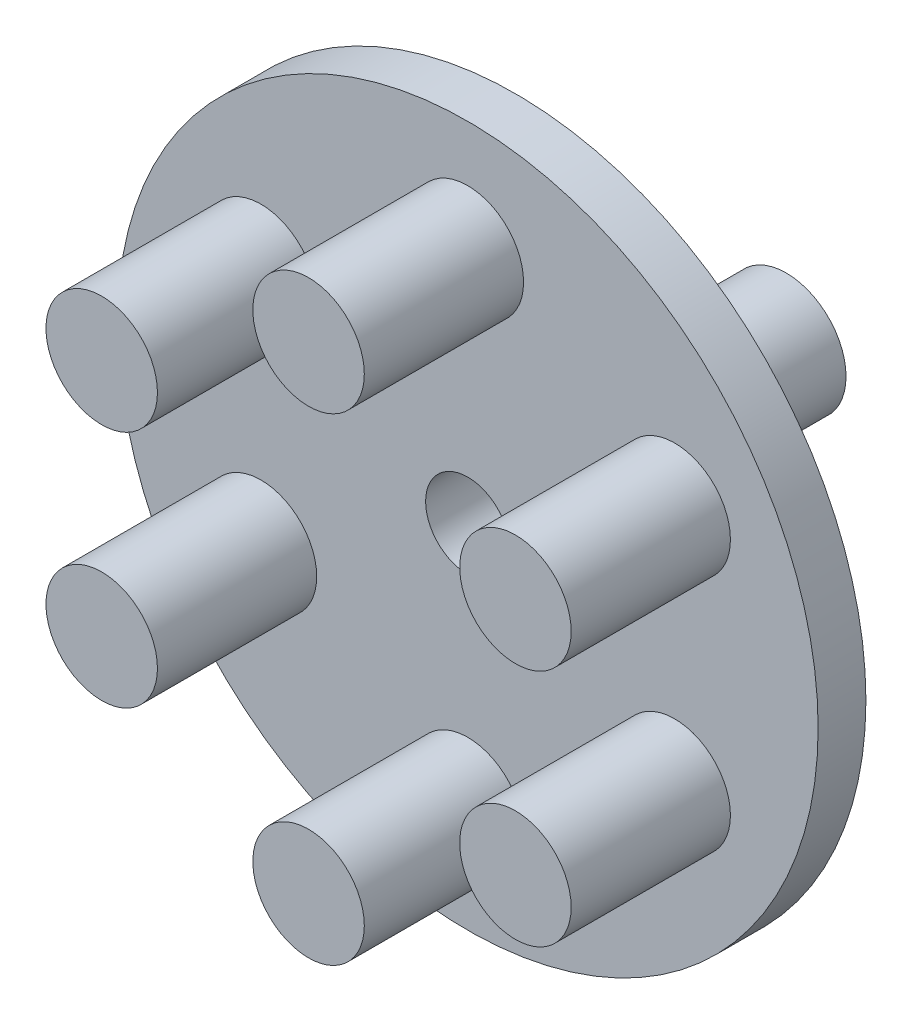
SolidWorks part; units mm, degrees
ref_plane "Front Plane" through (0, 0, 0) normal (0, 0, 1) x (1, 0, 0)
ref_plane "Top Plane" through (0, 0, 0) normal (0, 1, 0) x (1, 0, 0)
ref_plane "Right Plane" through (0, 0, 0) normal (1, 0, 0) x (0, 0, -1)
sketch "Sketch1" plane through (0, 0, 0) normal (0, 0, 1) x (1, 0, 0)
  circle A0 centre (0, 0) radius 22
  circle A1 centre (0, 0) radius 2.65
  dimension "D1" = 44
  dimension "D2" = 5.3
extrude "Boss-Extrude1" add sketch "Sketch1" along normal blind 3
sketch "Sketch2" plane through (0, 0, 3) normal (0, 0, 1) x (1, 0, 0)
  line L0 (0, -1.65) -> (0, 1.65) construction
  circle A0 centre (0, 15) radius 3.5
  circle A1 centre (12.9904, 7.5) radius 3.5
  circle A2 centre (12.9904, -7.5) radius 3.5
  circle A3 centre (0, -15) radius 3.5
  circle A4 centre (-12.9904, -7.5) radius 3.5
  circle A5 centre (-12.9904, 7.5) radius 3.5
  circle A6 centre (0, 0) radius 22 construction
  point P18 (0, 0)
  dimension "D1" = 7
  dimension "D2" = 15
  dimension "D4" = 12.9904
  dimension "D3" = 6
extrude "Boss-Extrude2" add sketch "Sketch2" along normal blind 10
sketch "Sketch3" plane through (0, 0, 0) normal (0, 0, -1) x (-1, 0, 0)
  circle A0 centre (0, 0) radius 2.65
  circle A1 centre (0, 0) radius 3.75
  dimension "D1" = 7.5
extrude "Boss-Extrude3" add sketch "Sketch3" along normal blind 17
